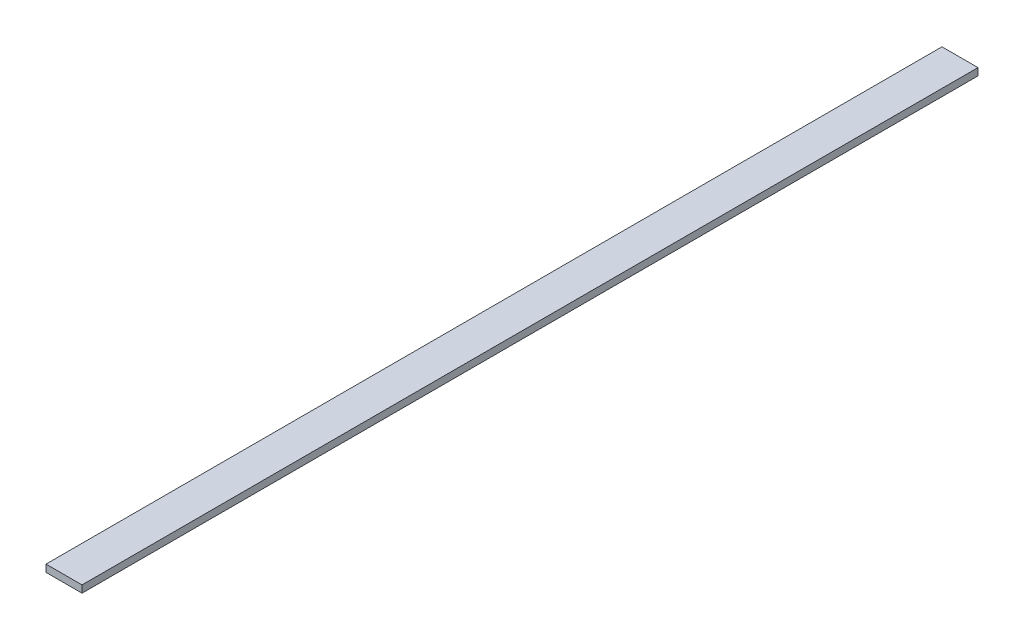
SolidWorks part; units mm, degrees
material "6061 Alloy"
ref_plane "Front Plane" through (0, 0, 0) normal (0, 0, 1) x (1, 0, 0)
ref_plane "Top Plane" through (0, 0, 0) normal (0, 1, 0) x (1, 0, 0)
ref_plane "Right Plane" through (0, 0, 0) normal (1, 0, 0) x (0, 0, -1)
sketch "Sketch1" plane through (0, 0, 0) normal (0, 0, 1) x (1, 0, 0)
  line L0 (6.25, 2.5) -> (6.25, 0) construction
  line L1 (0, 0) -> (12.5, 0)
  line L2 (0, 0) -> (0, 2.5)
  line L3 (0, 2.5) -> (12.5, 2.5)
  line L4 (12.5, 0) -> (12.5, 2.5)
  dimension "D1" = 12.5
  dimension "D2" = 2.5
extrude "Boss-Extrude1" add sketch "Sketch1" along normal blind 311
sketch "Sketch3" plane through (0, 2.5, 0) normal (0, 1, 0) x (1, 0, 0)
  line L0 (6.323, 0) -> (6.323, -37) construction
  line L1 (12.5, 0) -> (0, 0) construction
  point P4 (0, 0)
  point P5 (0, 0)
  dimension "D1" = 37
  dimension "D2" = 0
sketch "Sketch4" plane through (0, 0, 0) normal (0, -1, 0) x (1, 0, 0)
  line L0 (0, 311) -> (12.5, 311) construction
  line L1 (0.75, 314) -> (11.75, 314)
  line L2 (0.75, 314) -> (0.75, 293)
  line L3 (0.75, 293) -> (11.75, 293)
  line L4 (11.75, 314) -> (11.75, 293)
  line L5 (6.25, 314) -> (6.25, 311) construction
  point P6 (6.25, 311)
  point P7 (6.25, 314)
  dimension "D1" = 21
  dimension "D2" = 11
  dimension "D3" = 3
  dimension "D4" = 0
